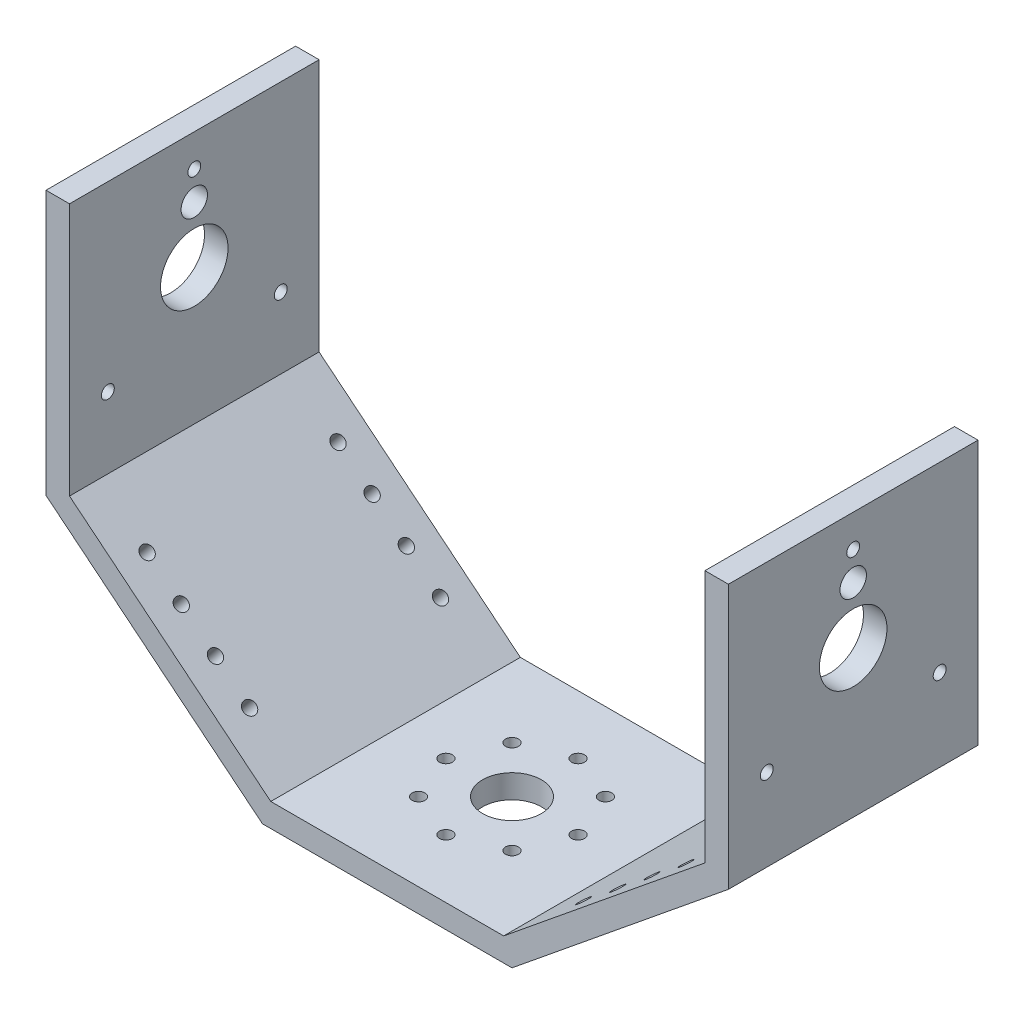
SolidWorks part; units mm, degrees
ref_plane "Front Plane" through (0, 0, 0) normal (0, 0, 1) x (1, 0, 0)
ref_plane "Top Plane" through (0, 0, 0) normal (0, 1, 0) x (1, 0, 0)
ref_plane "Right Plane" through (0, 0, 0) normal (1, 0, 0) x (0, 0, -1)
sketch "Sketch1" plane through (0, 0, 0) normal (0, 1, 0) x (1, 0, 0)
  line L1 (-116.2, 42.5) -> (116.2, 42.5)
  line L2 (-116.2, 42.5) -> (-116.2, -42.5)
  line L3 (-116.2, -42.5) -> (116.2, -42.5)
  line L4 (116.2, 42.5) -> (116.2, -42.5)
  line L5 (-116.2, 42.5) -> (116.2, -42.5) construction
  line L6 (-116.2, -42.5) -> (116.2, 42.5) construction
  point P0 (0, 0)
  dimension "D1" = 232.4
  dimension "D2" = 85
extrude "Boss-Extrude1" add sketch "Sketch1" along normal blind 150
sketch "Sketch2" plane through (0, 0, 42.5) normal (0, 0, 1) x (1, 0, 0)
  line L0 (-116.2, 0) -> (-116.2, 60)
  line L1 (46.75, 0) -> (-46.75, 0) construction
  line L2 (-116.2, 150) -> (-116.2, 0) construction
  line L3 (-116.2, 60) -> (-42.5, 0)
  line L4 (-42.5, 0) -> (-116.2, 0)
  line L5 (0, -46.75) -> (0, 46.75) construction
  line L6 (116.2, 60) -> (42.5, 0)
  line L7 (116.2, 0) -> (116.2, 60)
  line L8 (42.5, 0) -> (116.2, 0)
  dimension "D1" = 90
  dimension "D2" = 42.5
extrude "Cut-Extrude1" cut sketch "Sketch2" against normal blind 150
sketch "Sketch3" plane through (0, 0, 42.5) normal (0, 0, 1) x (1, 0, 0)
  line L11 (-108.2, 142) -> (-108.2, 150)
  line L12 (-116.2, 150) -> (116.2, 150) construction
  line L13 (-108.2, 150) -> (108.2, 150)
  line L14 (108.2, 150) -> (108.2, 142)
  line L17 (-39.6553, 8) -> (39.6553, 8)
  line L18 (108.2, 142) -> (-108.2, 142)
  line L19 (108.2, 63.803) -> (108.2, 142)
  line L20 (39.6553, 8) -> (108.2, 63.803)
  line L21 (-108.2, 63.803) -> (-39.6553, 8)
  line L22 (-108.2, 142) -> (-108.2, 63.803)
  line L23 (-39.6553, 8) -> (39.6553, 8)
  line L25 (108.2, 63.803) -> (108.2, 142)
  line L26 (39.6553, 8) -> (108.2, 63.803)
  line L27 (-108.2, 63.803) -> (-39.6553, 8)
  line L28 (-108.2, 142) -> (-108.2, 63.803)
  dimension "D1" = 8
extrude "Cut-Extrude2" cut sketch "Sketch3" against normal blind 150
sketch "Sketch4" plane through (-116.2, 0, 0) normal (-1, 0, 0) x (0, 0, 1)
  line L0 (0, -82.5) -> (0, 82.5) construction
  line L1 (-42.5, 150) -> (42.5, 150) construction
  circle A0 centre (0, 110) radius 11.5
  circle A1 centre (0, 139) radius 2.2
  circle A2 centre (0, 129.25) radius 4.5
  circle A3 centre (29.4449, 88) radius 2.2
  circle A4 centre (-29.4449, 88) radius 2.2
  point P16 (0, 105)
  dimension "D1" = 23
  dimension "D4" = 4.4
  dimension "D5" = 9
  dimension "D2" = 40
  dimension "D3" = 29
  dimension "D6" = 19.25
  dimension "D7" = 3
extrude "Cut-Extrude3" cut sketch "Sketch4" against normal through all
sketch "Sketch5" plane through (0, 8, 0) normal (0, 1, 0) x (1, 0, 0)
  line L0 (0, -46.75) -> (0, 46.75) construction
  circle A0 centre (0, 0) radius 10
  circle A1 centre (0, 22.5) radius 2.2
  circle A2 centre (15.9099, 15.9099) radius 2.2
  circle A3 centre (22.5, 0) radius 2.2
  circle A4 centre (15.9099, -15.9099) radius 2.2
  circle A5 centre (0, -22.5) radius 2.2
  circle A6 centre (-15.9099, -15.9099) radius 2.2
  circle A7 centre (-22.5, 0) radius 2.2
  circle A8 centre (-15.9099, 15.9099) radius 2.2
  point P24 (0, 0)
  dimension "D1" = 20
  dimension "D3" = 4.4
  dimension "D2" = 22.5
  dimension "D4" = 8
extrude "Cut-Extrude4" cut sketch "Sketch5" against normal through all
sketch "Sketch6" plane through (-16.9404, -20.8084, 0) normal (-0.6313, -0.7755, 0) x (0.7755, -0.6313, 0)
  line L0 (-127.994, -42.5) -> (-127.994, 42.5) construction
  line L1 (-32.9588, 42.5) -> (-127.994, 42.5) construction
  line L2 (82.5, 0) -> (-82.5, 0) construction
  circle A0 centre (-102.994, 32.5) radius 2.2
  circle A1 centre (-87.994, 32.5) radius 2.2
  circle A2 centre (-72.994, 32.5) radius 2.2
  circle A3 centre (-57.994, 32.5) radius 2.2
  circle A4 centre (-57.994, -32.5) radius 2.2
  circle A5 centre (-72.994, -32.5) radius 2.2
  circle A6 centre (-87.994, -32.5) radius 2.2
  circle A7 centre (-102.994, -32.5) radius 2.2
  dimension "D3" = 4.4
  dimension "D1" = 25
  dimension "D2" = 10
  dimension "D4" = 4
extrude "Cut-Extrude5" cut sketch "Sketch6" against normal through all
mirror "Mirror1" about plane through (0, 0, 0) normal (1, 0, 0) of "Cut-Extrude5"
